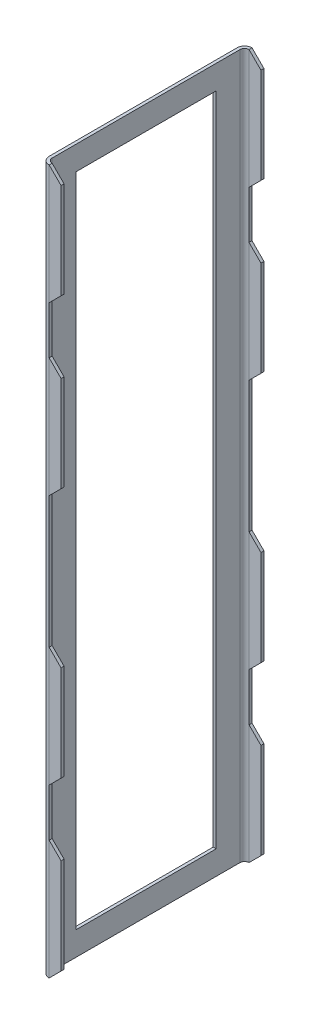
SolidWorks part; units mm, degrees
material "6061-T6 (SS)"
ref_plane "Front Plane" through (0, 0, 0) normal (0, 0, 1) x (1, 0, 0)
ref_plane "Top Plane" through (0, 0, 0) normal (0, 1, 0) x (1, 0, 0)
ref_plane "Right Plane" through (0, 0, 0) normal (1, 0, 0) x (0, 0, -1)
sketch "Sketch1" plane through (0, 0, 0) normal (0, 1, 0) x (1, 0, 0)
  line L0 (-51.5874, 0) -> (49.9999, 0) construction
  line L1 (-49.9999, -49.9999) -> (49.9999, -49.9999) construction
  line L2 (-49.9999, -49.9999) -> (-49.9999, 49.9999) construction
  line L3 (-49.9999, 49.9999) -> (49.9999, 49.9999) construction
  line L4 (49.9999, -49.9999) -> (49.9999, 49.9999) construction
  line L5 (-49.9999, -49.9999) -> (-51.5874, -49.9999) construction
  line L6 (-49.9999, 49.9999) -> (-49.9999, -49.9999)
  line L7 (-41.2686, -53.9686) -> (-41.2686, -52.3812)
  line L8 (-51.5874, 49.9999) -> (-51.5874, -49.9999)
  line L9 (-47.6186, -52.3811) -> (-41.2686, -52.3812)
  line L10 (-47.6186, -53.9686) -> (-41.2686, -53.9686)
  line L11 (-47.6186, 53.9686) -> (-41.2686, 53.9686)
  line L13 (-47.6186, 52.3811) -> (-41.2686, 52.3812)
  line L14 (-41.2686, 53.9686) -> (-41.2686, 52.3812)
  arc A0 (-47.6186, 52.3811) -> (-49.9999, 49.9999) centre (-47.6186, 49.9999) ccw
  arc A1 (-47.6186, 52.3811) -> (-49.9999, 49.9999) centre (-47.6186, 49.9999) ccw
  arc A2 (-47.6186, 53.9686) -> (-51.5874, 49.9999) centre (-47.6186, 49.9999) ccw
  arc A3 (-47.6186, -53.9686) -> (-51.5874, -49.9999) centre (-47.6186, -49.9999) cw
  arc A4 (-47.6186, -52.3811) -> (-49.9999, -49.9999) centre (-47.6186, -49.9999) cw
  arc A5 (-47.6186, -52.3811) -> (-49.9999, -49.9999) centre (-47.6186, -49.9999) cw
  circle A6 centre (0, 0) radius 76.2 construction
  dimension "D9" = 3.9688
  dimension "D7" = 152.4
  dimension "D1" = 49.9999
  dimension "D2" = 49.9999
  dimension "D3" = 6.35
  dimension "D4" = 49.9999
  dimension "D5" = 49.9999
  dimension "D6" = 1.5875
extrude "MainPlateExtrude" add sketch "Sketch1" along normal blind 374.65 contours L9 A4 L6 A0 L13 L14 L11 A2 L8 A3 L10 L7
sketch "Sketch2" plane through (0, 0, 53.9686) normal (0, 0, 1) x (1, 0, 0)
  line L0 (-47.6186, 374.65) -> (-41.2686, 368.3)
  line L1 (-41.2686, 374.65) -> (-41.2686, 0) construction
  line L2 (-47.6186, 285.75) -> (-41.2686, 279.4)
  line L3 (-47.6186, 374.65) -> (-47.6186, 0) construction
  line L4 (-41.2686, 317.5) -> (-47.6186, 311.15)
  line L5 (-47.6186, 374.65) -> (-41.2686, 374.65)
  line L6 (-41.2686, 374.65) -> (-41.2686, 368.3)
  line L7 (-41.2686, 317.5) -> (-41.2686, 0)
  line L8 (-41.2686, 0) -> (-47.6186, 0)
  line L9 (-47.6186, 0) -> (-41.2686, 6.35)
  line L10 (-47.6186, 63.5) -> (-41.2686, 57.15)
  line L11 (-47.6186, 88.9) -> (-41.2686, 95.25)
  line L12 (-47.6186, 152.4) -> (-41.2686, 146.05)
  line L13 (-47.6186, 222.25) -> (-41.2686, 228.6)
  line L14 (-47.6186, 311.15) -> (-47.6186, 285.75)
  line L15 (-47.6186, 222.25) -> (-47.6186, 152.4)
  line L16 (-47.6186, 88.9) -> (-47.6186, 63.5)
  line M9 (-47.6186, 0) -> (-41.2686, 0)
  line M10 (-41.2686, 0) -> (-41.2686, 374.65)
  line M11 (-41.2686, 374.65) -> (-47.6186, 374.65)
  line M12 (-47.6186, 374.65) -> (-47.6186, 0)
  dimension "D1" = 45
  dimension "D2" = 50.8
  dimension "D3" = 45
  dimension "D4" = 45
  dimension "D5" = 50.8
  dimension "D6" = 45
  dimension "D7" = 25.4
  dimension "D8" = 45
  dimension "D9" = 25.4
  dimension "D10" = 45
  dimension "D11" = 50.8
  dimension "D12" = 45
  dimension "D13" = 50.8
extrude "FlangeCut" cut sketch "Sketch2" against normal blind 107.95 contours L11 L10 M12 M10 | L9 M9 M10 | L13 L12 M12 M10 | L4 L2 M10 M12 | L0 M11 M10
sketch "Sketch3" plane through (-51.5874, 0, 0) normal (-1, 0, 0) x (0, 0, 1)
  line L0 (-37.2999, 361.95) -> (-37.2999, 12.7)
  line L1 (-49.9999, 374.65) -> (49.9999, 374.65) construction
  line L2 (-49.9999, 374.65) -> (-49.9999, 0) construction
  line L3 (-49.9999, 0) -> (49.9999, 0) construction
  line L4 (49.9999, 374.65) -> (49.9999, 0) construction
  line L5 (-37.2999, 12.7) -> (37.2999, 12.7)
  line L6 (37.2999, 361.95) -> (37.2999, 12.7)
  line L7 (-37.2999, 361.95) -> (37.2999, 361.95)
  dimension "D1" = 12.7
extrude "Cut-Extrude2" cut sketch "Sketch3" against normal blind 1.5875
